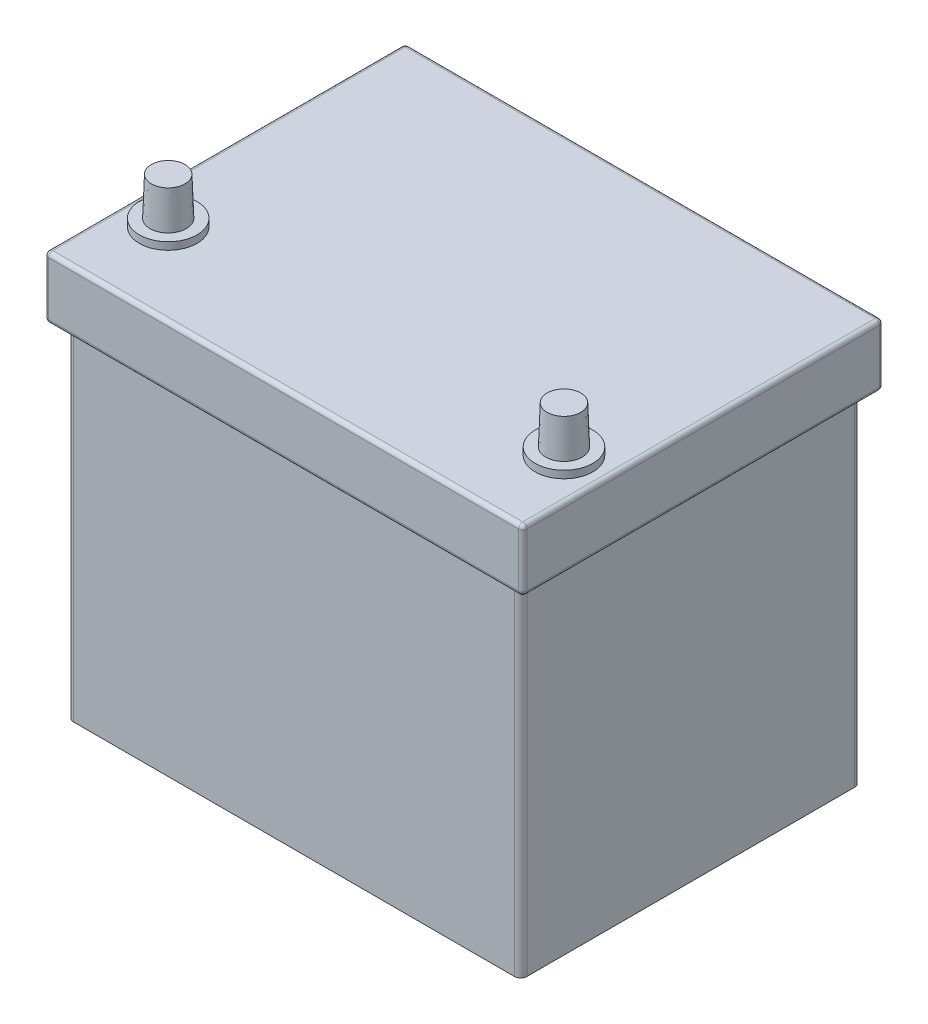
SolidWorks part; units mm, degrees
ref_plane "Спереди" through (0, 0, 0) normal (0, 0, 1) x (1, 0, 0)
ref_plane "Сверху" through (0, 0, 0) normal (0, 1, 0) x (1, 0, 0)
ref_plane "Справа" through (0, 0, 0) normal (1, 0, 0) x (0, 0, -1)
sketch "Эскиз1" plane through (0, 0, 0) normal (0, 1, 0) x (1, 0, 0)
  line L1 (-110, 82.5) -> (110, 82.5)
  line L2 (-110, 82.5) -> (-110, -82.5)
  line L3 (-110, -82.5) -> (110, -82.5)
  line L4 (110, 82.5) -> (110, -82.5)
  line L5 (-110, 82.5) -> (110, -82.5) construction
  line L6 (-110, -82.5) -> (110, 82.5) construction
  point P0 (0, 0)
  dimension "D1" = 110
  dimension "D2" = 82.5
extrude "Вытянуть1" add sketch "Эскиз1" along normal blind 166
fillet "Скругление1" radius 3 4 edges at (-110, 83, -82.5) (110, 83, -82.5) (110, 83, 82.5) (-110, 83, 82.5)
sketch "Эскиз2" plane through (0, 166, 0) normal (0, 1, 0) x (1, 0, 0)
  line L0 (110, -79.5) -> (110, 79.5) construction
  line L1 (-116, 87.5) -> (116, 87.5)
  line L2 (-116, 87.5) -> (-116, -87.5)
  line L3 (-116, -87.5) -> (116, -87.5)
  line L4 (116, 87.5) -> (116, -87.5)
  line L5 (-116, 87.5) -> (116, -87.5) construction
  line L6 (-116, -87.5) -> (116, 87.5) construction
  line L7 (107, 82.5) -> (-107, 82.5) construction
  point P0 (0, 0)
  dimension "D1" = 6
  dimension "D2" = 5
extrude "Вытянуть2" add sketch "Эскиз2" along normal blind 30
fillet "Скругление2" radius 2 12 edges at (116, 166, 0) (116, 181, 87.5) (0, 196, 87.5) (-116, 181, 87.5) (-116, 196, 0) (-116, 181, -87.5) (0, 196, -87.5) (116, 196, 0) (116, 181, -87.5) (0, 166, -87.5) (-116, 166, 0) (0, 166, 87.5)
sketch "Эскиз3" plane through (0, 196, 0) normal (0, 1, 0) x (1, 0, 0)
  line L3 (116, -87.5) -> (116, 87.5) construction
  line L4 (116, 87.5) -> (-116, 87.5) construction
  line L5 (0, 0) -> (0, -97.2203) construction
  circle A0 centre (96, -47.5) radius 14
  circle A1 centre (-96, -47.5) radius 14
  dimension "D1" = 28
  dimension "D2" = 20
  dimension "D3" = 135
  dimension "D4" = 212
extrude "Вытянуть3" add sketch "Эскиз3" along normal blind 3.6
sketch "Эскиз5" plane through (0, 199.6, 0) normal (0, 1, 0) x (1, 0, 0)
  circle A0 centre (96, -47.5) radius 8.8
  circle A1 centre (-96, -47.5) radius 8.8
  dimension "D1" = 17.6
  dimension "D2" = 17.6
extrude "Вытянуть4" add sketch "Эскиз5" along normal blind 18.5 draft 2
sketch "Эскиз7" plane through (0, 0, 0) normal (0, 1, 0) x (1, 0, 0)
  line L0 (0, 0) -> (151.4943, 0) construction
  line L1 (0, 0) -> (0, -98.7141) construction
